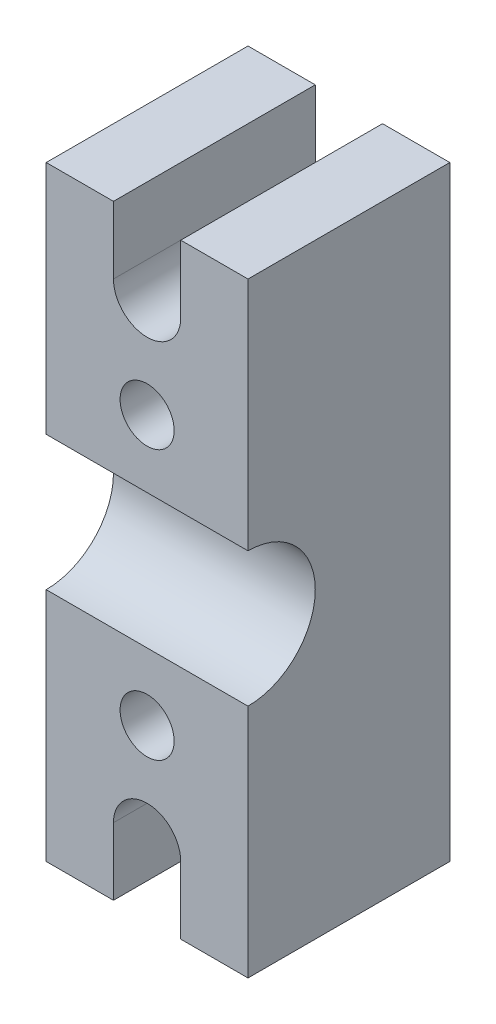
SolidWorks part; units mm, degrees
material "6061 Alloy"
ref_plane "Front Plane" through (0, 0, 0) normal (0, 0, 1) x (1, 0, 0)
ref_plane "Top Plane" through (0, 0, 0) normal (0, 1, 0) x (1, 0, 0)
ref_plane "Right Plane" through (0, 0, 0) normal (1, 0, 0) x (0, 0, -1)
sketch "Sketch1" plane through (0, 0, 0) normal (0, 0, 1) x (1, 0, 0)
  line L0 (-3.175, -28.575) -> (-3.175, -22.225)
  line L1 (9.525, -28.575) -> (3.175, -28.575)
  line L2 (9.525, -28.575) -> (9.525, 28.575)
  line L3 (9.525, 28.575) -> (3.175, 28.575)
  line L4 (-9.525, -28.575) -> (-9.525, 28.575)
  line L5 (9.525, -28.575) -> (-9.525, 28.575) construction
  line L6 (9.525, 28.575) -> (-9.525, -28.575) construction
  line L7 (3.175, -22.225) -> (3.175, -28.575)
  line L8 (0, -28.575) -> (0, -22.225) construction
  line L9 (-3.175, -28.575) -> (-9.525, -28.575)
  line L10 (0, 0) -> (0, -22.225) construction
  line L11 (0, 0) -> (20.0792, 0) construction
  line L12 (3.175, 22.225) -> (3.175, 28.575)
  line L13 (-3.175, 28.575) -> (-3.175, 22.225)
  line L14 (-3.175, 28.575) -> (-9.525, 28.575)
  arc A0 (-3.175, -22.225) -> (3.175, -22.225) centre (0, -22.225) cw
  arc A1 (-3.175, 22.225) -> (3.175, 22.225) centre (0, 22.225) ccw
  point P0 (0, 0)
  dimension "D1" = 19.05
  dimension "D2" = 57.15
  dimension "D3" = 6.35
  dimension "D4" = 6.35
extrude "Boss-Extrude1" add sketch "Sketch1" along normal blind 19.05
hole_wizard "1/4-20 Tapped Hole1" positions "Sketch2" profile "Sketch3" tap size "1/4-20" standard "ANSI Inch"
sketch "Sketch2" plane through (0, 0, 19.05) normal (0, 0, 1) x (1, 0, 0)
  line L0 (0, 6.35) -> (0, 19.05) construction
  line L4 (0, -6.35) -> (0, -19.05) construction
  circle A0 centre (0, 0) radius 6.35 construction
  arc A1 (-3.175, 22.225) -> (3.175, 22.225) centre (0, 22.225) ccw construction
  arc A3 (3.175, -22.225) -> (-3.175, -22.225) centre (0, -22.225) ccw construction
  point P0 (0, 12.7)
  point P2 (0, -12.7)
  point P16 (0, 12.7)
  dimension "D1" = 12.7
sketch "Sketch3" plane through (0, 12.7, 19.05) normal (1, 0, 0) x (0, -1, 0)
  line L0 (0, 0) -> (0, 18.0438)
  line L1 (0, 18.0438) -> (2.5527, 16.51)
  line L2 (2.5527, 16.51) -> (2.5527, 0)
  line L5 (2.5527, 0) -> (0, 0)
  line L10 (0, 18.0438) -> (-2.5527, 16.51) construction
  line L11 (0, -6.35) -> (0, 107.95) construction
  dimension "Tap Drill Dia." = 5.1054
  dimension "Tap Drill Depth" = 16.51
  dimension "Drill Angle" = 118
cosmetic thread "Hole Thread1" parameters "D1"=12.7, "D2"=6.35
cosmetic thread "Hole Thread2" parameters "D1"=12.7, "D2"=6.35
sketch "Sketch4" plane through (9.525, 0, 0) normal (1, 0, 0) x (0, 0, -1)
  line L0 (-19.05, -28.575) -> (-19.05, 28.575) construction
  circle A0 centre (-19.05, 0) radius 6.35
  dimension "D1" = 12.7
extrude "Cut-Extrude1" cut sketch "Sketch4" against normal blind 19.05
